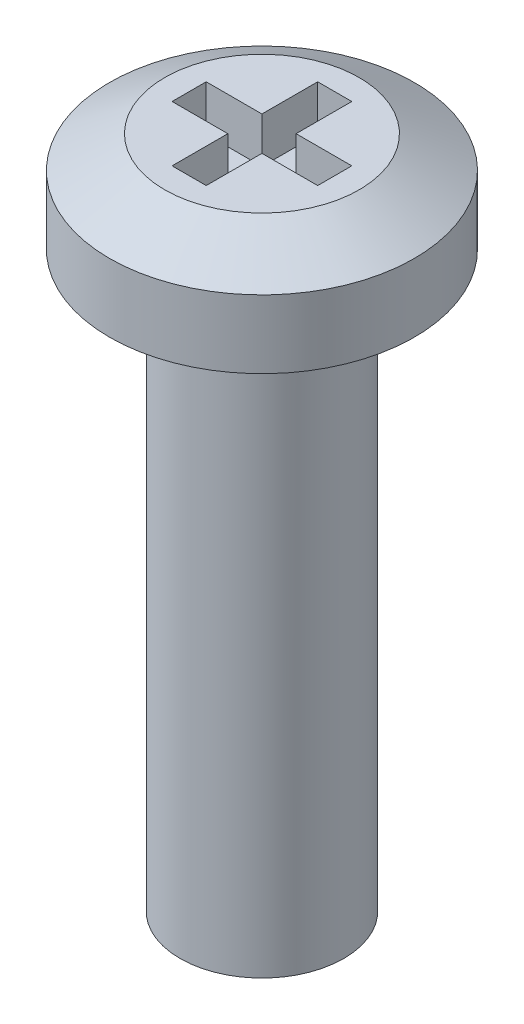
SolidWorks part; units mm, degrees
material "Plain Carbon Steel"
ref_plane "Front Plane" through (0, 0, 0) normal (0, 0, 1) x (1, 0, 0)
ref_plane "Top Plane" through (0, 0, 0) normal (0, 1, 0) x (1, 0, 0)
ref_plane "Right Plane" through (0, 0, 0) normal (1, 0, 0) x (0, 0, -1)
sketch "Sketch1" plane through (0, 0, 0) normal (0, 1, 0) x (1, 0, 0)
  circle A0 centre (0, 0) radius 3.35
  dimension "D1" = 6.7
extrude "Boss-Extrude1" add sketch "Sketch1" along normal blind 1.5 contours A0
sketch "Sketch2" plane through (0, 1.5, 0) normal (0, 1, 0) x (1, 0, 0)
  circle A0 centre (0, 0) radius 3.35 construction
  circle A1 centre (0, 0) radius 3.35
extrude "Boss-Extrude2" add sketch "Sketch2" along normal blind 0.7 draft 60
sketch "Sketch3" plane through (0, 2.2, 0) normal (0, 1, 0) x (1, 0, 0)
  line L1 (-0.375, -1.6) -> (0.375, -1.6)
  line L2 (-0.375, -1.6) -> (-0.375, 1.6)
  line L3 (-0.375, 1.6) -> (0.375, 1.6)
  line L4 (0.375, -1.6) -> (0.375, 1.6)
  line L5 (-0.375, -1.6) -> (0.375, 1.6) construction
  line L6 (-0.375, 1.6) -> (0.375, -1.6) construction
  line L7 (-1.6, -0.375) -> (1.6, -0.375)
  line L8 (-1.6, -0.375) -> (-1.6, 0.375)
  line L9 (-1.6, 0.375) -> (1.6, 0.375)
  line L10 (1.6, -0.375) -> (1.6, 0.375)
  line L11 (-1.6, -0.375) -> (1.6, 0.375) construction
  line L12 (-1.6, 0.375) -> (1.6, -0.375) construction
  point P0 (0, 0)
  point P6 (0, 0)
  dimension "D1" = 3.2
  dimension "D2" = 3.2
  dimension "D3" = 0.75
  dimension "D4" = 0.75
extrude "Cut-Extrude1" cut sketch "Sketch3" against normal blind 1 contours L9 L8 L7 L2 | L2 L9 L4 L3 | L7 L10 L9 L4 | L7 L2 L1 L4 | L9 L2 L7 L4
sketch "Sketch4" plane through (0, 0, 0) normal (0, -1, 0) x (1, 0, 0)
  circle A0 centre (0, 0) radius 1.8
  dimension "D1" = 3.6
extrude "Boss-Extrude3" add sketch "Sketch4" along normal blind 12.6
